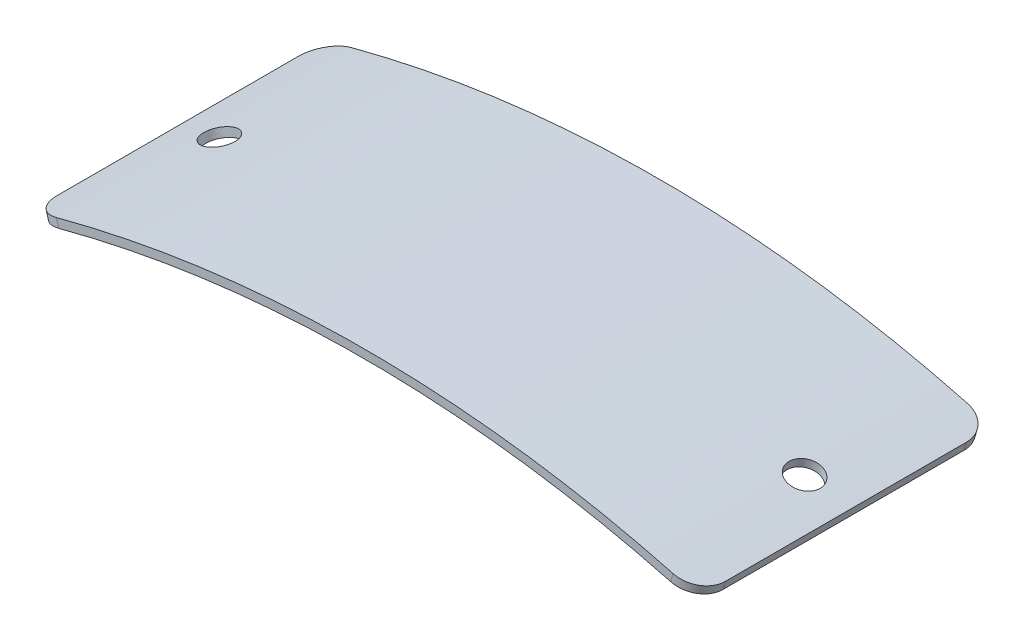
SolidWorks part; units mm, degrees
ref_plane "正面" through (0, 0, 0) normal (0, 0, 1) x (1, 0, 0)
ref_plane "平面" through (0, 0, 0) normal (0, 1, 0) x (1, 0, 0)
ref_plane "右側面" through (0, 0, 0) normal (1, 0, 0) x (0, 0, -1)
sketch "ｽｹｯﾁ1" plane through (0, 0, 0) normal (0, 0, 1) x (1, 0, 0)
  line L0 (61.949, 214.2226) -> (62.3935, 215.7596)
  line L1 (-62.3935, 215.7596) -> (-61.949, 214.2226)
  arc A0 (62.3935, 215.7596) -> (-62.3935, 215.7596) centre (0, 0) ccw
  arc A1 (61.949, 214.2226) -> (-61.949, 214.2226) centre (0, 0) ccw
extrude "ﾎﾞｽ - 押し出し1" add sketch "ｽｹｯﾁ1" along normal blind 55
fillet "ﾌｨﾚｯﾄ1" radius 5 4 edges at (62.1712, 214.9911, 0) (-62.1712, 214.9911, 0) (62.1712, 214.9911, 55) (-62.1712, 214.9911, 55)
ref_plane "平面1" through (0, 0, 27.5) normal (0, 0, 1) x (1, 0, 0)
sketch "ｽｹｯﾁ2" plane through (0, 0, 27.5) normal (0, 0, 1) x (1, 0, 0)
  line L0 (51.5286, 205.4362) -> (57.3675, 228.7151)
  line L1 (57.3675, 228.7151) -> (54.4576, 229.445)
  line L2 (54.4576, 229.445) -> (48.6187, 206.1661)
  line L3 (48.6187, 206.1661) -> (51.5286, 205.4362)
  line L4 (51.5286, 205.4362) -> (57.3675, 228.7151) construction
revolve "ｶｯﾄ - 回転1" cut sketch "ｽｹｯﾁ2" angle 360 about L4
sketch "ｽｹｯﾁ3" plane through (0, 0, 27.5) normal (0, 0, 1) x (1, 0, 0)
  line L0 (-51.5286, 205.4362) -> (-57.3675, 228.7151)
  line L1 (-57.3675, 228.7151) -> (-60.2774, 227.9853)
  line L2 (-60.2774, 227.9853) -> (-54.4384, 204.7064)
  line L3 (-54.4384, 204.7064) -> (-51.5286, 205.4362)
  line L4 (-51.5286, 205.4362) -> (-57.3675, 228.7151) construction
revolve "ｶｯﾄ - 回転2" cut sketch "ｽｹｯﾁ3" angle 360 about L4
